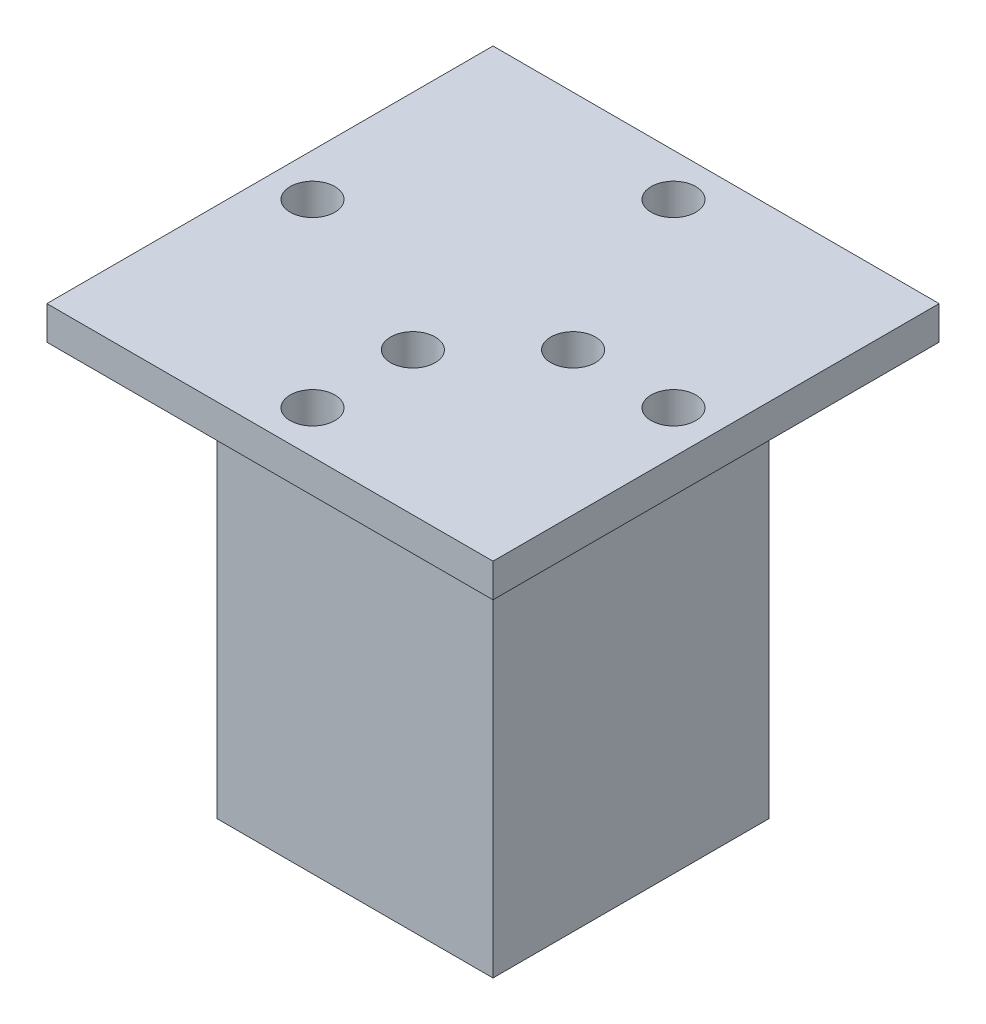
SolidWorks part; units mm, degrees
ref_plane "Front Plane" through (0, 0, 0) normal (0, 0, 1) x (1, 0, 0)
ref_plane "Top Plane" through (0, 0, 0) normal (0, 1, 0) x (1, 0, 0)
ref_plane "Right Plane" through (0, 0, 0) normal (1, 0, 0) x (0, 0, -1)
ref_plane "Plane1" through (0, -2.667, 0) normal (0, -1, 0) x (1, 0, 0)
sketch "Sketch1" plane through (0, -2.667, 0) normal (0, -1, 0) x (1, 0, 0)
  line L0 (-96.9645, -58.801) -> (96.9645, -58.801)
  line L1 (96.9645, -58.801) -> (96.9645, 58.801)
  line L2 (96.9645, 58.801) -> (-96.9645, 58.801)
  line L3 (-96.9645, 58.801) -> (-96.9645, -58.801)
extrude "Boss-Extrude1" add sketch "Sketch1" against normal blind 2.667
sketch "Sketch2" plane through (0, -2.667, 0) normal (0, -1, 0) x (1, 0, 0)
  line L0 (-74.4728, 55.3085) -> (-93.472, 36.2712)
  line L1 (-93.472, 36.2712) -> (-93.472, -36.2712)
  line L2 (-93.472, -36.2712) -> (-74.4728, -55.3085)
  line L3 (-74.4728, -55.3085) -> (74.4728, -55.3085)
  line L4 (74.4728, -55.3085) -> (93.472, -36.2712)
  line L5 (93.472, -36.2712) -> (93.472, 36.2712)
  line L6 (93.472, 36.2712) -> (74.4728, 55.3085)
  line L7 (74.4728, 55.3085) -> (-74.4728, 55.3085)
extrude "Cut-Extrude1" cut sketch "Sketch2" against normal blind 0.254
sketch "Sketch3" plane through (0, -2.413, 0) normal (0, -1, 0) x (1, 0, 0)
  line L0 (92.6846, 35.9455) -> (92.6846, -35.9455)
  line L1 (92.6846, -35.9455) -> (74.1462, -54.5211)
  line L2 (74.1462, -54.5211) -> (-74.1462, -54.5211)
  line L3 (-74.1462, -54.5211) -> (-92.6846, -35.9455)
  line L4 (-92.6846, -35.9455) -> (-92.6846, 35.9455)
  line L5 (-92.6846, 35.9455) -> (-74.1462, 54.5211)
  line L6 (-74.1462, 54.5211) -> (74.1462, 54.5211)
  line L7 (74.1462, 54.5211) -> (92.6846, 35.9455)
extrude "Boss-Extrude2" add sketch "Sketch3" along normal blind 0.254
sketch "Sketch4" plane through (0, 0, 0) normal (0, 1, 0) x (-1, 0, 0)
  line L0 (92.6211, -49.3395) -> (92.6211, 49.3395)
  line L1 (94.2213, 49.3395) -> (94.2213, -49.3395)
  arc A0 (92.6211, 49.3395) -> (94.2213, 49.3395) centre (93.4212, 49.3395) cw
  arc A1 (94.2213, -49.3395) -> (92.6211, -49.3395) centre (93.4212, -49.3395) cw
extrude "Boss-Extrude3" add sketch "Sketch4" along normal blind 1.6002
sketch "Sketch5" plane through (0, 0, 0) normal (0, 1, 0) x (-1, 0, 0)
  line L0 (-94.2213, -49.3395) -> (-94.2213, 49.3395)
  line L1 (-92.6211, 49.3395) -> (-92.6211, -49.3395)
  arc A0 (-94.2213, 49.3395) -> (-92.6211, 49.3395) centre (-93.4212, 49.3395) cw
  arc A1 (-92.6211, -49.3395) -> (-94.2213, -49.3395) centre (-93.4212, -49.3395) cw
extrude "Boss-Extrude4" add sketch "Sketch5" along normal blind 1.6002
sketch "Sketch6" plane through (0, 0, 0) normal (0, 1, 0) x (-1, 0, 0)
  line L0 (10.4013, -54.4576) -> (87.5919, -54.4576)
  line L1 (87.5919, -56.0578) -> (10.4013, -56.0578)
  arc A0 (87.5919, -54.4576) -> (87.5919, -56.0578) centre (87.5919, -55.2577) cw
  arc A1 (10.4013, -56.0578) -> (10.4013, -54.4576) centre (10.4013, -55.2577) cw
extrude "Boss-Extrude5" add sketch "Sketch6" along normal blind 1.6002
sketch "Sketch7" plane through (0, 0, 0) normal (0, 1, 0) x (-1, 0, 0)
  line L0 (-87.5919, 56.0578) -> (87.5919, 56.0578)
  line L1 (87.5919, 54.4576) -> (-87.5919, 54.4576)
  arc A0 (87.5919, 56.0578) -> (87.5919, 54.4576) centre (87.5919, 55.2577) cw
  arc A1 (-87.5919, 54.4576) -> (-87.5919, 56.0578) centre (-87.5919, 55.2577) cw
extrude "Boss-Extrude6" add sketch "Sketch7" along normal blind 1.6002
sketch "Sketch8" plane through (0, 0, 0) normal (0, 1, 0) x (-1, 0, 0)
  line L0 (-87.5919, -54.4576) -> (-10.4013, -54.4576)
  line L1 (-10.4013, -56.0578) -> (-87.5919, -56.0578)
  arc A0 (-10.4013, -54.4576) -> (-10.4013, -56.0578) centre (-10.4013, -55.2577) cw
  arc A1 (-87.5919, -56.0578) -> (-87.5919, -54.4576) centre (-87.5919, -55.2577) cw
extrude "Boss-Extrude7" add sketch "Sketch8" along normal blind 1.6002
ref_plane "Plane2" through (0, 0, -50.038) normal (0, 0, 1) x (1, 0, 0)
sketch "Sketch9" plane through (0, 0, -50.038) normal (0, 0, 1) x (1, 0, 0)
  line L0 (-84.455, 3.175) -> (-88.138, 3.175)
  line L1 (-88.138, 3.175) -> (-88.138, 0)
  line L2 (-88.138, 0) -> (-84.455, 0)
  line L3 (-84.455, 0) -> (-84.455, 3.175)
  line L4 (-88.138, 3.175) -> (-88.138, 0) construction
revolve "Revolve1" add sketch "Sketch9" angle 360 about L4
ref_plane "Plane3" through (0, 0, 50.038) normal (0, 0, 1) x (1, 0, 0)
sketch "Sketch10" plane through (0, 0, 50.038) normal (0, 0, 1) x (1, 0, 0)
  line L0 (91.821, 3.175) -> (88.138, 3.175)
  line L1 (88.138, 3.175) -> (88.138, 0)
  line L2 (88.138, 0) -> (91.821, 0)
  line L3 (91.821, 0) -> (91.821, 3.175)
  line L4 (88.138, 3.175) -> (88.138, 0) construction
revolve "Revolve2" add sketch "Sketch10" angle 360 about L4
sketch "Sketch11" plane through (0, 0, 50.038) normal (0, 0, 1) x (1, 0, 0)
  line L0 (-84.455, 3.175) -> (-88.138, 3.175)
  line L1 (-88.138, 3.175) -> (-88.138, 0)
  line L2 (-88.138, 0) -> (-84.455, 0)
  line L3 (-84.455, 0) -> (-84.455, 3.175)
  line L4 (-88.138, 3.175) -> (-88.138, 0) construction
revolve "Revolve3" add sketch "Sketch11" angle 360 about L4
sketch "Sketch12" plane through (0, 0, -50.038) normal (0, 0, 1) x (1, 0, 0)
  line L0 (91.821, 3.175) -> (88.138, 3.175)
  line L1 (88.138, 3.175) -> (88.138, 0)
  line L2 (88.138, 0) -> (91.821, 0)
  line L3 (91.821, 0) -> (91.821, 3.175)
  line L4 (88.138, 3.175) -> (88.138, 0) construction
revolve "Revolve4" add sketch "Sketch12" angle 360 about L4
hole_wizard "CSK for M3 Flat Head Machine Screw1" positions "Sketch14" profile "Sketch13" countersink size "M3" standard "ANSI Metric"
sketch "Sketch14" plane through (0, -2.667, 0) normal (0, -1, 0) x (-1, 0, 0)
  point P0 (-88.138, 50.038)
  point P1 (88.138, -50.038)
  point P2 (88.138, 50.038)
  point P3 (-88.138, -50.038)
sketch "Sketch13" plane through (88.138, -2.667, -50.038) normal (1, 0, 0) x (0, 0, -1)
  line L0 (0, 0) -> (0, 5.842)
  line L1 (0, 5.842) -> (1.6256, 5.842)
  line L2 (1.6256, 5.842) -> (1.6256, 3.175)
  line L3 (1.6256, 3.175) -> (3.048, 1.5387)
  line L4 (3.048, 1.5387) -> (3.048, 0)
  line L6 (3.048, 0) -> (0, 0)
  line L7 (-1.6256, 3.175) -> (-3.048, 1.5387) construction
  line L11 (0, -6.35) -> (0, 107.95) construction
  dimension "Thru Hole Dia." = 3.2512
  dimension "Thru Hole Depth" = 5.842
  dimension "C'Sink Dia." = 6.096
  dimension "C'Sink Angle" = 82
  dimension "Head Clearance" = 1.5387
fillet "Fillet1" radius 5.1562 4 edges at (-96.9645, -1.3335, 58.801) (-96.9645, -1.3335, -58.801) (96.9645, -1.3335, 58.801) (96.9645, -1.3335, -58.801)
fillet "Fillet2" radius 1.5748 8 edges at (-95.4543, -2.667, 57.2908) (0, -2.667, 58.801) (-96.9645, -2.667, 0) (95.4543, -2.667, 57.2908) (-95.4543, -2.667, -57.2908) (96.9645, -2.667, 0) (0, -2.667, -58.801) (95.4543, -2.667, -57.2908)
fillet "Fillet3" radius 3.9624 8 edges at (-92.6846, -2.54, -35.9455) (-74.1462, -2.54, 54.5211) (-74.1462, -2.54, -54.5211) (74.1462, -2.54, 54.5211) (-92.6846, -2.54, 35.9455) (92.6846, -2.54, -35.9455) (92.6846, -2.54, 35.9455) (74.1462, -2.54, -54.5211)
fillet "Fillet4" radius 4.7498 8 edges at (-93.472, -2.54, 36.2712) (-93.472, -2.54, -36.2712) (74.4728, -2.54, -55.3085) (-74.4728, -2.54, -55.3085) (-74.4728, -2.54, 55.3085) (93.472, -2.54, -36.2712) (93.472, -2.54, 36.2712) (74.4728, -2.54, 55.3085)
sketch "Sketch16" plane through (0, -2.667, 0) normal (0, -1, 0) x (1, 0, 0)
  line L1 (-20, -20) -> (20, -20)
  line L2 (-20, -20) -> (-20, 20)
  line L3 (-20, 20) -> (20, 20)
  line L4 (20, -20) -> (20, 20)
  line L5 (-20, -20) -> (20, 20) construction
  line L6 (-20, 20) -> (20, -20) construction
  line L7 (-12.3639, -12.3639) -> (12.3639, -12.3639)
  line L8 (-12.3639, -12.3639) -> (-12.3639, 12.3639)
  line L9 (-12.3639, 12.3639) -> (12.3639, 12.3639)
  line L10 (12.3639, -12.3639) -> (12.3639, 12.3639)
  line L11 (-12.3639, -12.3639) -> (12.3639, 12.3639) construction
  line L12 (-12.3639, 12.3639) -> (12.3639, -12.3639) construction
  point P0 (0, 0)
  point P6 (0, 0)
  dimension "D1" = 40
  dimension "D2" = 40
  dimension "D3" = 24.7277
extrude "Boss-Extrude8" add sketch "Sketch16" along normal blind 40 contours L7 L10 L9 L8
sketch "Sketch18" plane through (0, -2.667, 0) normal (0, -1, 0) x (1, 0, 0)
  line L1 (-20, 20) -> (20, 20)
  line L2 (-20, 20) -> (-20, -20)
  line L3 (-20, -20) -> (20, -20)
  line L4 (20, 20) -> (20, -20)
  line L5 (-12.3639, 12.3639) -> (12.3639, 12.3639)
  line L6 (-12.3639, 12.3639) -> (-12.3639, -12.3639)
  line L7 (-12.3639, -12.3639) -> (12.3639, -12.3639)
  line L8 (12.3639, 12.3639) -> (12.3639, -12.3639)
extrude "Boss-Extrude9" add sketch "Sketch18" along normal blind 3
sketch "Sketch17" plane through (0, -2.667, 0) normal (0, -1, 0) x (1, 0, 0)
  circle A0 centre (-16.1819, 0) radius 2
  circle A1 centre (0, 16.1819) radius 2
  circle A2 centre (16.1819, 0) radius 2
  circle A3 centre (0, -16.1819) radius 2
  point P26 (0, 0)
  dimension "D1" = 4
extrude "Cut-Extrude2" cut sketch "Sketch17" against normal blind 40 and the other way blind 40
sketch "Sketch19" plane through (0, -42.667, 0) normal (0, -1, 0) x (1, 0, 0)
  circle A0 centre (0, 0) radius 2
extrude "Cut-Extrude3" cut sketch "Sketch19" against normal blind 10
sketch "Sketch20" plane through (0, -2.667, 0) normal (0, -1, 0) x (1, 0, 0)
  line L0 (-55.827, 33.2231) -> (42.4771, 33.2231)
  line L1 (42.4771, 33.2231) -> (42.4771, -37.1675)
  line L2 (42.4771, -37.1675) -> (-55.827, -37.1675)
  line L3 (-55.827, -37.1675) -> (-55.827, 33.2231)
  line L5 (-108.9234, 68.7219) -> (117.7222, 68.7219)
  line L6 (-108.9234, 68.7219) -> (-108.9234, -70.5423)
  line L7 (-108.9234, -70.5423) -> (117.7222, -70.5423)
  line L8 (117.7222, 68.7219) -> (117.7222, -70.5423)
extrude "Cut-Extrude4" cut sketch "Sketch20" against normal through all
sketch "Sketch21" plane through (0, 0, -37.1675) normal (0, 0, -1) x (-1, 0, 0)
  line L1 (55.827, -2.667) -> (-42.4771, -2.667)
  line L2 (55.827, -2.667) -> (55.827, 0)
  line L3 (55.827, 0) -> (-42.4771, 0)
  line L4 (-42.4771, -2.667) -> (-42.4771, 0)
extrude "Cut-Extrude5" cut sketch "Sketch21" against normal through all
sketch "Sketch23" plane through (0, -42.667, 0) normal (0, -1, 0) x (1, 0, 0)
  circle A2 centre (7.1819, 0) radius 2
  circle A3 centre (0, 7.1819) radius 2
extrude "Cut-Extrude6" cut sketch "Sketch23" against normal through all
